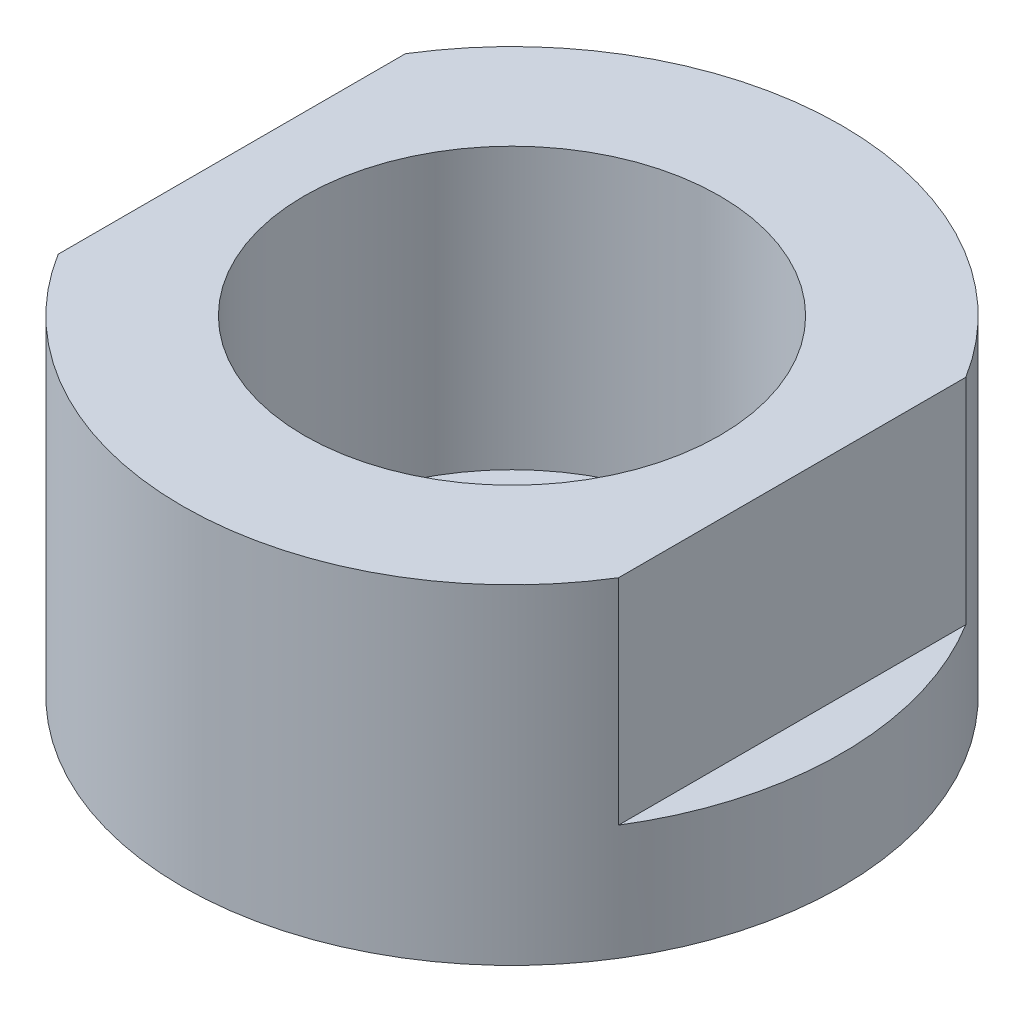
SolidWorks part; units mm, degrees
ref_plane "Front Plane" through (0, 0, 0) normal (0, 0, 1) x (1, 0, 0)
ref_plane "Top Plane" through (0, 0, 0) normal (0, 1, 0) x (1, 0, 0)
ref_plane "Right Plane" through (0, 0, 0) normal (1, 0, 0) x (0, 0, -1)
sketch "Sketch1" plane through (0, 0, 0) normal (0, 1, 0) x (1, 0, 0)
  circle A0 centre (0, 0) radius 25.4
  dimension "D1" = 50.8
extrude "Boss-Extrude1" add sketch "Sketch1" along normal blind 25.4
sketch "Sketch2" plane through (0, 25.4, 0) normal (0, 1, 0) x (1, 0, 0)
  circle A0 centre (0, 0) radius 16
  dimension "D1" = 32
extrude "Cut-Extrude1" cut sketch "Sketch2" against normal offset from surface (21.59 mm away) 3.81 up to face at (0, 0, 25.4)
sketch "Sketch3" plane through (0, 0, 0) normal (0, 0, 1) x (1, 0, 0)
  line L1 (25.4, 25.4) -> (21.59, 25.4)
  line L2 (25.4, 25.4) -> (25.4, 8.89)
  line L3 (25.4, 8.89) -> (21.59, 8.89)
  line L4 (21.59, 25.4) -> (21.59, 8.89)
  line L5 (25.4, 25.4) -> (21.59, 8.89) construction
  line L6 (25.4, 8.89) -> (21.59, 25.4) construction
  line L7 (-25.4, 25.4) -> (-21.59, 25.4)
  line L8 (-25.4, 25.4) -> (-25.4, 8.89)
  line L9 (-25.4, 8.89) -> (-21.59, 8.89)
  line L10 (-21.59, 25.4) -> (-21.59, 8.89)
  line L11 (-25.4, 25.4) -> (-21.59, 8.89) construction
  line L12 (-25.4, 8.89) -> (-21.59, 25.4) construction
  point P4 (23.495, 17.145)
  point P10 (-23.495, 17.145)
  dimension "D1" = 16.51
  dimension "D2" = 3.81
extrude "Cut-Extrude2" cut sketch "Sketch3" against normal up to next and the other way up to next
sketch "Sketch4" plane through (0, 3.81, 0) normal (0, 1, 0) x (1, 0, 0)
  line L0 (0, 0) -> (0, 8.89) construction
  circle A0 centre (0, 8.89) radius 1
  circle A1 centre (7.699, -4.445) radius 1
  circle A2 centre (-7.699, -4.445) radius 1
  point P11 (0, 0)
  dimension "D1" = 2
  dimension "D2" = 8.89
  dimension "D3" = 3
extrude "Cut-Extrude3" cut sketch "Sketch4" against normal up to next
